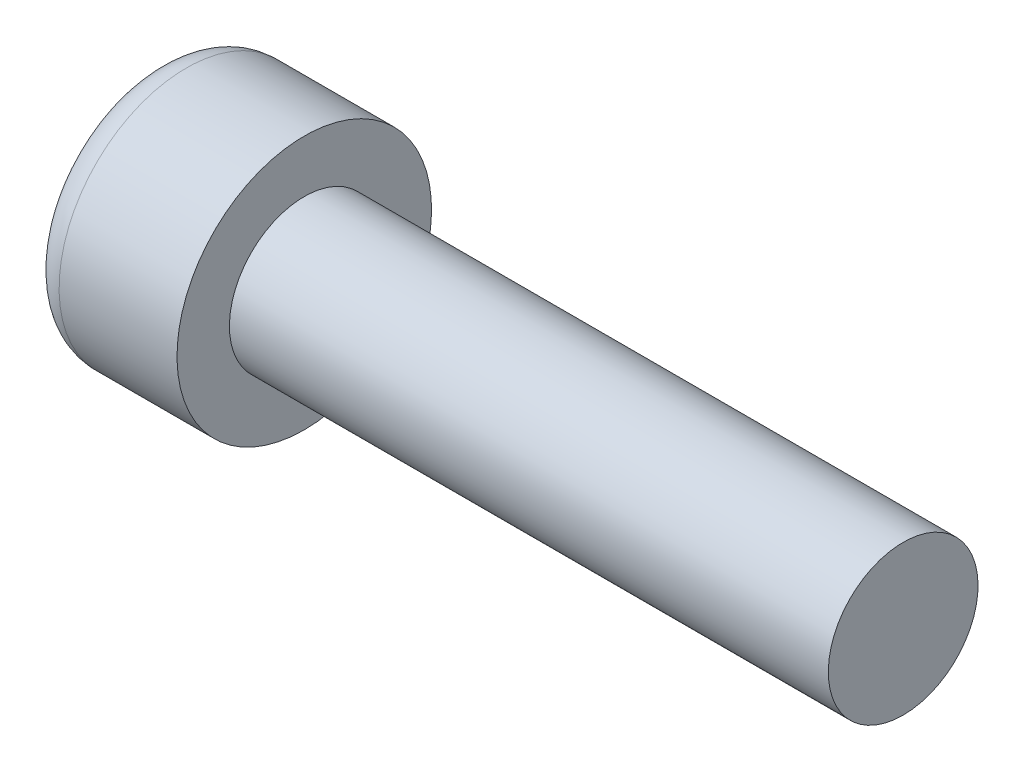
SolidWorks part; units mm, degrees
material "Plain Carbon Steel"
ref_plane "Front Plane" through (0, 0, 0) normal (0, 0, 1) x (1, 0, 0)
ref_plane "Top Plane" through (0, 0, 0) normal (0, 1, 0) x (1, 0, 0)
ref_plane "Right Plane" through (0, 0, 0) normal (1, 0, 0) x (0, 0, -1)
sketch "Sketch1" plane through (0, 0, 0) normal (0, 0, 1) x (1, 0, 0)
  line L0 (0, 0) -> (0, 3.1875)
  line L1 (1.0625, 4.25) -> (5, 4.25)
  line L2 (5, 4.25) -> (5, 2.5)
  line L3 (5, 2.5) -> (25, 2.5)
  line L4 (25, 2.5) -> (25, 0)
  line L5 (25, 0) -> (0, 0) construction
  line L6 (1.0625, 3.1875) -> (1.0625, 2.125) construction
  line L7 (1.0625, 2.125) -> (1.0625, 1.0625) construction
  line L8 (1.0625, 1.0625) -> (1.0625, 0) construction
  line L9 (1.0625, 4.25) -> (1.0625, 3.1875) construction
  line L10 (0, 0) -> (25, 0)
  arc A0 (0, 3.1875) -> (1.0625, 4.25) centre (1.0625, 3.1875) cw
  dimension "D1" = 5
  dimension "D2" = 8.5
  dimension "D3" = 5
  dimension "D4" = 20
revolve "Revolve1" add sketch "Sketch1" angle 360 about L10
sketch "Sketch2" plane through (0, 0, 0) normal (-1, 0, 0) x (0, 0, 1)
  line L1 (0, 2.3094) -> (-2, 1.1547)
  line L2 (-2, 1.1547) -> (-2, -1.1547)
  line L3 (-2, -1.1547) -> (0, -2.3094)
  line L4 (0, -2.3094) -> (2, -1.1547)
  line L5 (2, -1.1547) -> (2, 1.1547)
  line L6 (2, 1.1547) -> (0, 2.3094)
  circle A0 centre (0, 0) radius 2 construction
  dimension "D1" = 4
extrude "Cut-Extrude1" cut sketch "Sketch2" against normal blind 2.5
